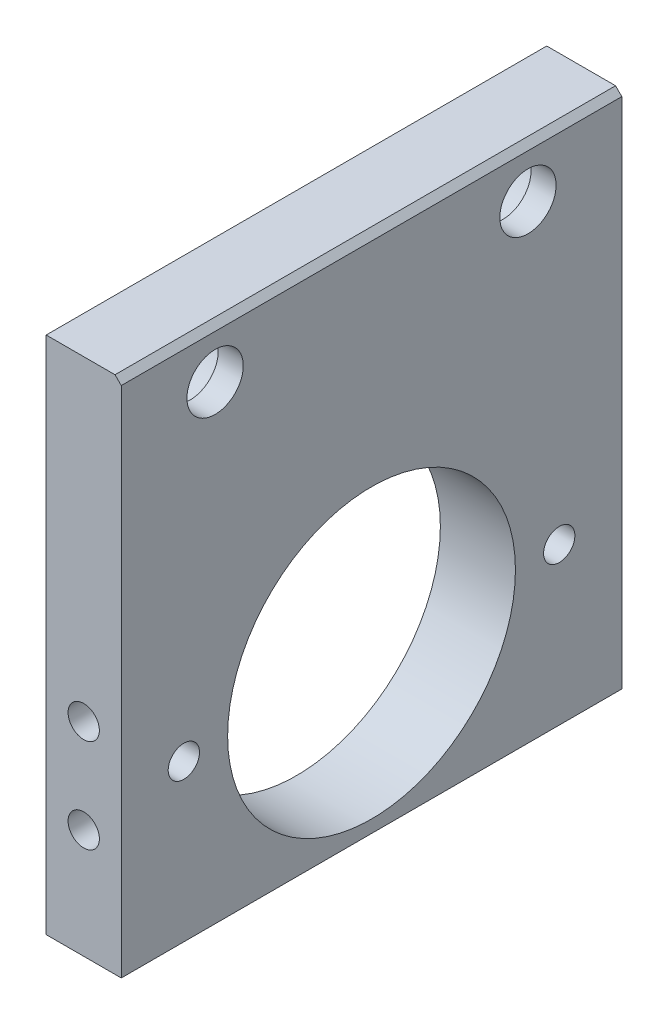
SolidWorks part; units mm, degrees
material "45#"
ref_plane "前视" through (0, 0, 0) normal (0, 0, 1) x (1, 0, 0)
ref_plane "上视" through (0, 0, 0) normal (0, 1, 0) x (1, 0, 0)
ref_plane "右视" through (0, 0, 0) normal (1, 0, 0) x (0, 0, -1)
sketch "草图1" plane through (0, 0, 0) normal (1, 0, 0) x (0, 0, -1)
  line L1 (-40, -41.5) -> (40, -41.5)
  line L2 (-40, -41.5) -> (-40, 41.5)
  line L3 (-40, 41.5) -> (40, 41.5)
  line L4 (40, -41.5) -> (40, 41.5)
  line L5 (-40, -41.5) -> (40, 41.5) construction
  line L6 (-40, 41.5) -> (40, -41.5) construction
  point P0 (0, 0)
  dimension "D1" = 80
  dimension "D2" = 83
extrude "凸台-拉伸1" add sketch "草图1" along normal blind 12
hole_wizard "打孔尺寸根据内六角圆柱头螺钉的类型1" positions "草图3" profile "草图2" counterbore size "M8" standard "Gb" end condition through all
sketch "草图3" plane through (0, 0, 0) normal (-1, 0, 0) x (0, 0, 1)
  line L0 (0, 41.5) -> (0, 24.3249) construction
  line L1 (-40, 41.5) -> (40, 41.5) construction
  point P0 (-25, 33.5)
  point P10 (25, 33.5)
  dimension "D1" = 50
  dimension "D2" = 8
sketch "草图2" plane through (0, 33.5, -25) normal (0, 1, 0) x (0, 0, 1)
  line L0 (0, 0) -> (0, 12)
  line L1 (0, 12) -> (4.5, 12)
  line L3 (4.5, 12) -> (4.5, 8)
  line L4 (4.5, 8) -> (7.5, 8)
  line L5 (7.5, 8) -> (7.5, 0)
  line L7 (7.5, 0) -> (0, 0)
  line L11 (0, -6.35) -> (0, 107.95) construction
  dimension "通孔孔直径" = 9
  dimension "通孔孔深度" = 12
  dimension "柱形沉头孔直径" = 15
  dimension "柱形沉头孔深度" = 8
hole_wizard "孔1" positions "草图5" profile "草图4" legacy end condition through all
sketch "草图5" plane through (12, 0, 0) normal (1, 0, 0) x (0, 0, -1)
  line L0 (0, 41.5) -> (0, -16.5) construction
  line L1 (40, 41.5) -> (-40, 41.5) construction
  line L2 (-40, -41.5) -> (40, -41.5) construction
  point P0 (0, -16.5)
  dimension "D1" = 25
sketch "草图4" plane through (12, -16.5, 0) normal (0, 1, 0) x (0, 0, -1)
  line L0 (0, 0) -> (0, 12)
  line L1 (0, 12) -> (23, 12)
  line L2 (23, 12) -> (23, 0)
  line L3 (23, 0) -> (0, 0)
  line L4 (0, 110) -> (0, -10) construction
  dimension "直径" = 46
  dimension "深度" = 12
hole_wizard "M6 螺纹孔2" positions "草图7" profile "草图6" tap size "M6" standard "Gb" end condition through all
sketch "草图7" plane through (0, 0, 0) normal (-1, 0, 0) x (0, 0, 1)
  line L0 (0, -16.5) -> (0, 24.8118) construction
  line L2 (0, -16.5) -> (45.8277, -16.5) construction
  point P0 (-30, -16.5)
  point P13 (30, -16.5)
  dimension "D2" = 60
sketch "草图6" plane through (0, -16.5, -30) normal (0, 1, 0) x (0, 0, 1)
  line L0 (0, 0) -> (0, 12)
  line L1 (0, 12) -> (2.5, 12)
  line L2 (2.5, 12) -> (2.5, 0)
  line L5 (2.5, 0) -> (0, 0)
  line L11 (0, -6.35) -> (0, 107.95) construction
  dimension "通孔螺纹孔钻头直径" = 5
  dimension "通孔螺纹孔钻头深度" = 12
cosmetic thread "孔螺蚊线3" parameters "D2"=6
cosmetic thread "孔螺蚊线4" parameters "D2"=6
hole_wizard "M6 螺纹孔1" positions "草图9" profile "草图8" tap size "M6" standard "Gb"
sketch "草图9" plane through (0, 0, -40) normal (0, 0, -1) x (-1, 0, 0)
  line L0 (-6, 41.5) -> (-6, -16.5) construction
  line L1 (-12, 41.5) -> (0, 41.5) construction
  line L2 (-6, -16.5) -> (9.0793, -16.5) construction
  line L5 (-12, -16.5) -> (0, -16.5) construction
  point P0 (-6, -9)
  point P15 (-6, -24)
  dimension "D1" = 15
sketch "草图8" plane through (6, -9, -40) normal (1, 0, 0) x (0, 1, 0)
  line L0 (0, 0) -> (0, 16.5022)
  line L1 (0, 16.5022) -> (2.5, 15)
  line L2 (2.5, 15) -> (2.5, 0)
  line L5 (2.5, 0) -> (0, 0)
  line L10 (0, 16.5022) -> (-2.5, 15) construction
  line L11 (0, -6.35) -> (0, 107.95) construction
  dimension "螺纹孔钻头直径" = 5
  dimension "螺纹孔钻头深度" = 15
  dimension "导头角度" = 118
cosmetic thread "孔螺蚊线1" parameters "D1"=12, "D2"=6
cosmetic thread "孔螺蚊线2" parameters "D1"=12, "D2"=6
mirror "镜向1" about plane through (0, 0, 0) normal (0, 0, 1) of "M6 螺纹孔1"
chamfer "倒角1" distance 1 angle 45 1 edges at (12, 41.5, 0)
